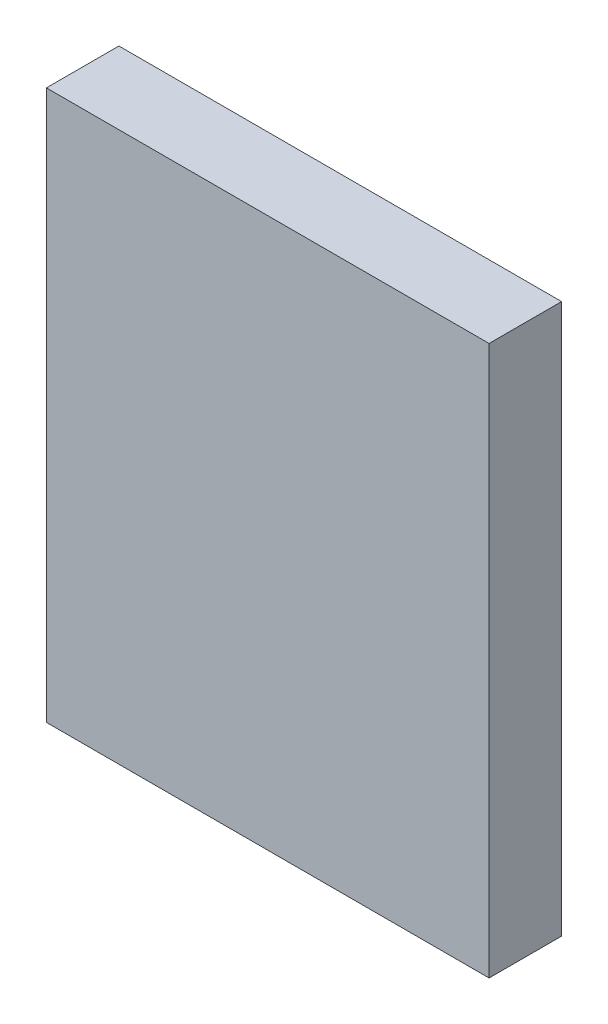
SolidWorks part; units mm, degrees
ref_plane "Plan de face" through (0, 0, 0) normal (0, 0, 1) x (1, 0, 0)
ref_plane "Plan de dessus" through (0, 0, 0) normal (0, 1, 0) x (1, 0, 0)
ref_plane "Plan de droite" through (0, 0, 0) normal (1, 0, 0) x (0, 0, -1)
sketch "Esquisse1" plane through (0, 0, 0) normal (0, 0, 1) x (1, 0, 0)
  line L1 (-14.3034, 13.0188) -> (14.6966, 13.0188)
  line L2 (-14.3034, 13.0188) -> (-14.3034, -22.9812)
  line L3 (-14.3034, -22.9812) -> (14.6966, -22.9812)
  line L4 (14.6966, 13.0188) -> (14.6966, -22.9812)
  dimension "D1" = 29
  dimension "D2" = 36
extrude "Boss.-Extru.1" add sketch "Esquisse1" along normal blind 4.75
